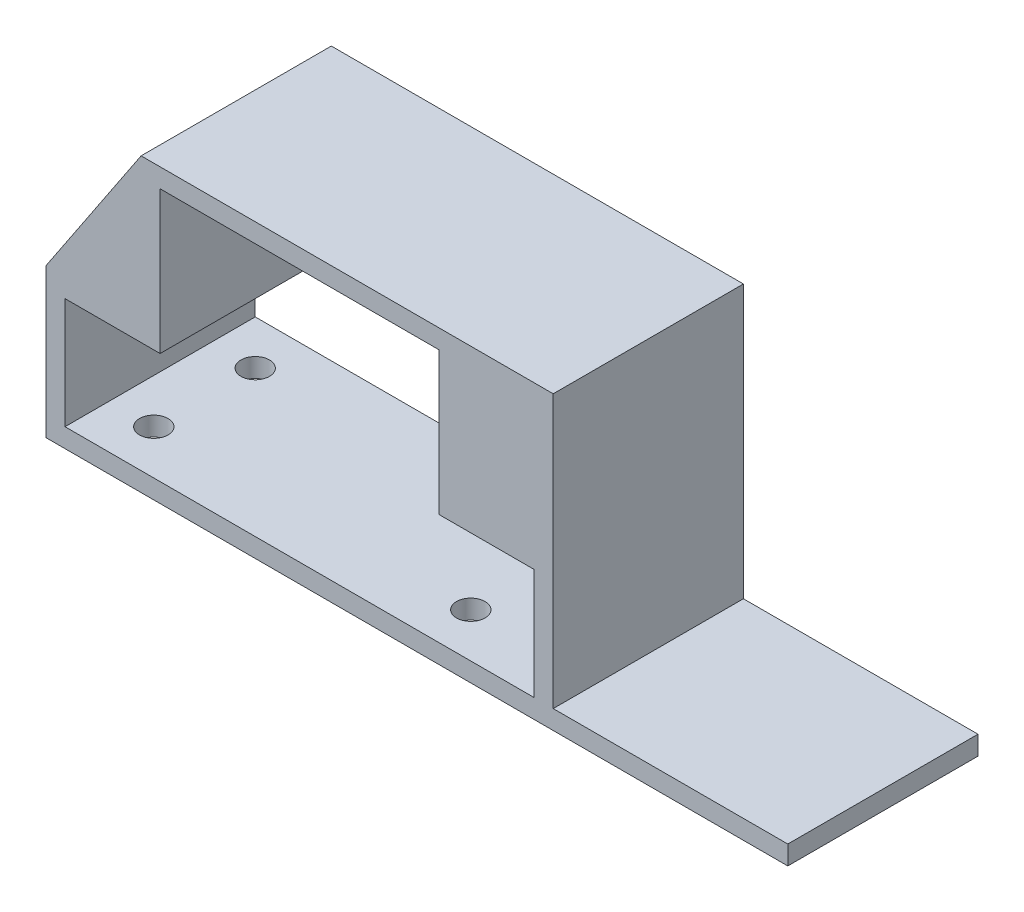
SolidWorks part; units mm, degrees
ref_plane "Front Plane" through (0, 0, 0) normal (0, 0, 1) x (1, 0, 0)
ref_plane "Top Plane" through (0, 0, 0) normal (0, 1, 0) x (1, 0, 0)
ref_plane "Right Plane" through (0, 0, 0) normal (1, 0, 0) x (0, 0, -1)
sketch "Sketch1" plane through (0, 0, 0) normal (0, 1, 0) x (1, 0, 0)
  line L0 (0, 16) -> (0, 0) construction
  line L1 (0, 0) -> (50, 0) construction
  line L2 (0, 16) -> (50, 16) construction
  line L3 (-7, 23) -> (-7, -7)
  line L4 (-7, 23) -> (57, 23)
  line L5 (50, 16) -> (56.5, 16) construction
  line L6 (57, -7) -> (-7, -7)
  line L7 (57, 23) -> (107, 23)
  line L8 (107, 23) -> (107, -7)
  line L9 (107, -7) -> (57, -7)
  line L10 (56.5, 16) -> (66.5, 16) construction
  circle A0 centre (0, 0) radius 2.25
  circle A1 centre (0, 16) radius 2.25
  circle A2 centre (50, 0) radius 2.25
  circle A3 centre (50, 16) radius 2.25
  point P11 (-7, 8)
  point P12 (0, 8)
  dimension "D1" = 4.5
  dimension "D2" = 16
  dimension "D3" = 50
  dimension "D4" = 30
  dimension "D5" = 7
  dimension "D6" = 6.5
  dimension "D7" = 50
  dimension "D8" = 10
extrude "Boss-Extrude1" add sketch "Sketch1" along normal blind 3
sketch "Sketch2" plane through (0, 0, -23) normal (0, 0, -1) x (-1, 0, 0)
  line L0 (7, 3) -> (7, 20.5)
  line L1 (-5, 46) -> (-70, 46)
  line L2 (-67, 3) -> (-70, 3)
  line L4 (-107, 3) -> (7, 3) construction
  line L6 (-52, 20.5) -> (-52, 43)
  line L7 (-52, 43) -> (-8, 43)
  line L8 (-8, 43) -> (-8, 20.5)
  line L9 (-10, -509) -> (-10, 41) construction
  line L10 (-50, 21) -> (-50, -479) construction
  line L11 (7, 3) -> (7, 0)
  line L12 (7, 0) -> (10, 0)
  line L13 (10, 0) -> (10, 23.5)
  line L14 (-52, 20.5) -> (-67, 20.5)
  line L15 (7, 20.5) -> (-8, 20.5)
  line L16 (5.5, 19.5) -> (-7.4, 19.5) construction
  line L17 (10, 23.5) -> (-5, 23.5)
  line L18 (-5, 23.5) -> (-5, 46)
  line L19 (-67, 20.5) -> (-67, 3)
  line L20 (-66.5, 4.2) -> (-66.5, 18.5) construction
  line L22 (-70, 3) -> (-70, 46)
  dimension "D2" = 2
  dimension "D3" = 2
  dimension "D4" = 2
  dimension "D5" = 3
  dimension "D6" = 1
  dimension "D7" = 3
  dimension "D8" = 3
  dimension "D9" = 3
  dimension "D10" = 0.5
  dimension "D11" = 3
extrude "Boss-Extrude2" add sketch "Sketch2" against normal blind 30
sketch "Sketch3" plane through (0, 0, -23) normal (0, 0, -1) x (-1, 0, 0)
  line L0 (-5, 46) -> (10, 23.5)
  line L1 (10, 23.5) -> (-5, 23.5)
  line L2 (-5, 23.5) -> (-5, 46)
extrude "Boss-Extrude3" add sketch "Sketch3" against normal blind 30
